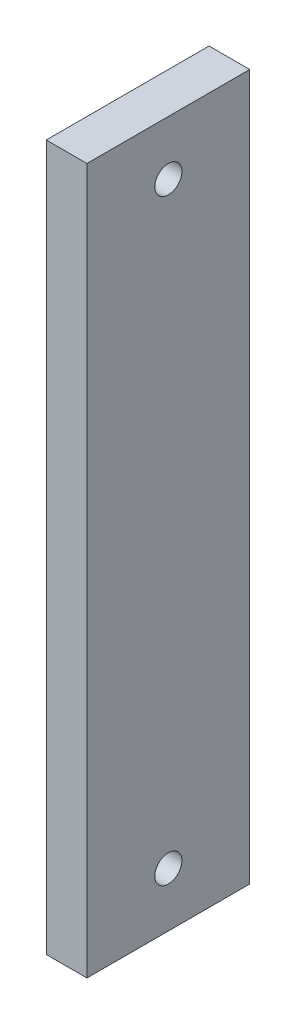
SolidWorks part; units mm, degrees
ref_plane "Front Plane" through (0, 0, 0) normal (0, 0, 1) x (1, 0, 0)
ref_plane "Top Plane" through (0, 0, 0) normal (0, 1, 0) x (1, 0, 0)
ref_plane "Right Plane" through (0, 0, 0) normal (1, 0, 0) x (0, 0, -1)
sketch "Sketch1" plane through (0, 0, 0) normal (0, 1, 0) x (1, 0, 0)
  line L1 (4.7625, 19.05) -> (-4.7625, 19.05)
  line L2 (4.7625, 19.05) -> (4.7625, -19.05)
  line L3 (4.7625, -19.05) -> (-4.7625, -19.05)
  line L4 (-4.7625, 19.05) -> (-4.7625, -19.05)
  line L5 (4.7625, 19.05) -> (-4.7625, -19.05) construction
  line L6 (4.7625, -19.05) -> (-4.7625, 19.05) construction
  point P0 (0, 0)
  dimension "D1" = 38.1
  dimension "D2" = 9.525
extrude "Boss-Extrude1" add sketch "Sketch1" along normal blind 165.1
sketch "Sketch2" plane through (4.7625, 0, 0) normal (1, 0, 0) x (0, 0, -1)
  line L0 (-19.05, 165.1) -> (19.05, 165.1) construction
  line L1 (-19.05, 165.1) -> (-19.05, 0) construction
  line L2 (-19.05, 0) -> (19.05, 0) construction
  circle A0 centre (0, 152.4) radius 3.175
  circle A1 centre (0, 12.7) radius 3.175
  dimension "D1" = 6.35
  dimension "D2" = 12.7
  dimension "D3" = 19.05
  dimension "D4" = 6.35
  dimension "D5" = 19.05
  dimension "D6" = 12.7
extrude "Cut-Extrude1" cut sketch "Sketch2" against normal blind 101.6
